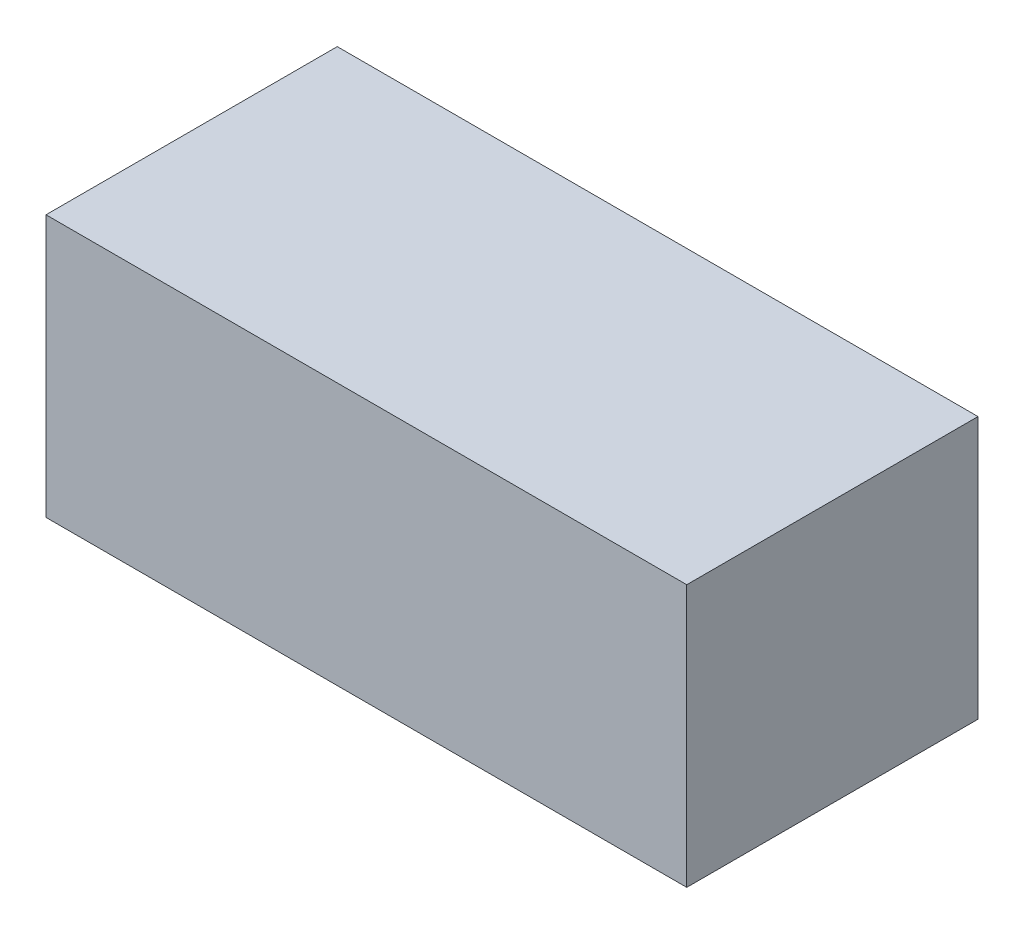
SolidWorks part; units mm, degrees
ref_plane "Front Plane" through (0, 0, 0) normal (0, 0, 1) x (1, 0, 0)
ref_plane "Top Plane" through (0, 0, 0) normal (0, 1, 0) x (1, 0, 0)
ref_plane "Right Plane" through (0, 0, 0) normal (1, 0, 0) x (0, 0, -1)
sketch "Sketch1" plane through (0, 0, 0) normal (0, 1, 0) x (1, 0, 0)
  line L1 (-11, 5) -> (11, 5)
  line L2 (-11, 5) -> (-11, -5)
  line L3 (-11, -5) -> (11, -5)
  line L4 (11, 5) -> (11, -5)
  line L5 (-11, 5) -> (11, -5) construction
  line L6 (-11, -5) -> (11, 5) construction
  point P0 (0, 0)
  dimension "D1" = 22
  dimension "D2" = 10
extrude "Boss-Extrude1" add sketch "Sketch1" along normal blind 9
